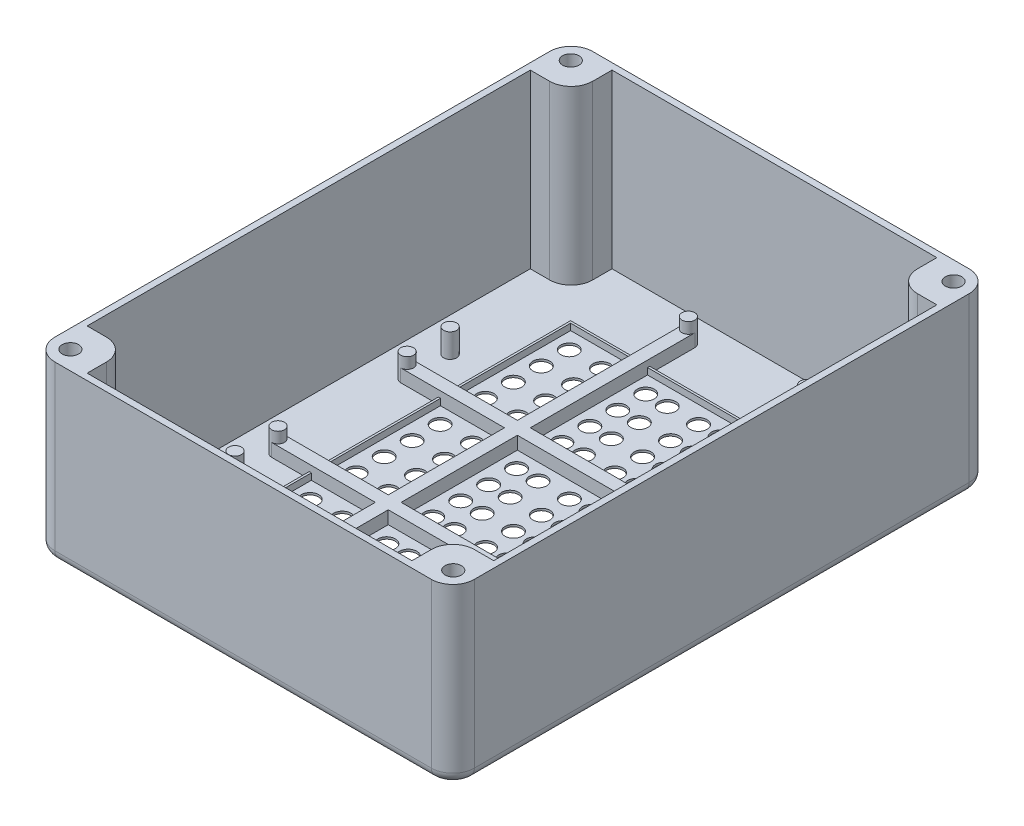
SolidWorks part; units mm, degrees
ref_plane "Front Plane" through (0, 0, 0) normal (0, 0, 1) x (1, 0, 0)
ref_plane "Top Plane" through (0, 0, 0) normal (0, 1, 0) x (1, 0, 0)
ref_plane "Right Plane" through (0, 0, 0) normal (1, 0, 0) x (0, 0, -1)
sketch "Sketch1" plane through (0, 0, 0) normal (0, 1, 0) x (1, 0, 0)
  line L1 (-97.5, 125) -> (97.5, 125)
  line L2 (-97.5, 125) -> (-97.5, -125)
  line L3 (-97.5, -125) -> (97.5, -125)
  line L4 (97.5, 125) -> (97.5, -125)
  line L5 (-97.5, 125) -> (97.5, -125) construction
  line L6 (-97.5, -125) -> (97.5, 125) construction
  line L7 (-94.5, -122) -> (94.5, -122)
  line L8 (-94.5, -122) -> (-94.5, 122)
  line L9 (-94.5, 122) -> (94.5, 122)
  line L10 (94.5, -122) -> (94.5, 122)
  line L11 (-94.5, -122) -> (94.5, 122) construction
  line L12 (-94.5, 122) -> (94.5, -122) construction
  point P0 (0, 0)
  point P6 (0, 0)
  dimension "D1" = 250
  dimension "D2" = 195
  dimension "D3" = 189
  dimension "D4" = 244
extrude "Boss-Extrude1" add sketch "Sketch1" along normal blind 80
sketch "Sketch2" plane through (0, 0, 0) normal (0, -1, 0) x (1, 0, 0)
  line L1 (-97.5, -125) -> (97.5, -125)
  line L2 (-97.5, -125) -> (-97.5, 125)
  line L3 (-97.5, 125) -> (97.5, 125)
  line L4 (97.5, -125) -> (97.5, 125)
  line L5 (-97.5, -125) -> (-97.5, 125) construction
  line L6 (97.5, 125) -> (75.5, 125)
  line L7 (97.5, 125) -> (97.5, 103)
  line L8 (97.5, 103) -> (75.5, 103)
  line L9 (75.5, 125) -> (75.5, 103)
  line L10 (97.5, -125) -> (75.5, -125)
  line L11 (97.5, -125) -> (97.5, -103)
  line L12 (97.5, -103) -> (75.5, -103)
  line L13 (75.5, -125) -> (75.5, -103)
  line L14 (-97.5, -125) -> (-75.5, -125)
  line L15 (-97.5, -125) -> (-97.5, -103)
  line L16 (-97.5, -103) -> (-75.5, -103)
  line L17 (-75.5, -125) -> (-75.5, -103)
  line L18 (-97.5, 125) -> (-75.5, 125)
  line L19 (-97.5, 125) -> (-97.5, 103)
  line L20 (-97.5, 103) -> (-75.5, 103)
  line L21 (-75.5, 125) -> (-75.5, 103)
  dimension "D1" = 22
  dimension "D2" = 22
  dimension "D3" = 22
  dimension "D4" = 22
  dimension "D5" = 22
  dimension "D6" = 22
  dimension "D7" = 22
  dimension "D8" = 22
extrude "Boss-Extrude2" add sketch "Sketch2" against normal blind 80 contours L13 L1 L4 L12 | L1 L17 L16 L2 | L21 L3 L2 L20 | L3 L9 L8 L4
sketch "Sketch4" plane through (0, 0, 0) normal (0, 1, 0) x (1, 0, 0)
  line L0 (-27.5, -109.5) -> (-60.5, -109.5)
  line L1 (-78.75, 30) -> (78.75, 30)
  line L2 (-78.75, 30) -> (-78.75, -30)
  line L3 (-78.75, -30) -> (78.75, -30)
  line L4 (78.75, 30) -> (78.75, -30)
  line L5 (-78.75, 30) -> (78.75, -30) construction
  line L6 (-78.75, -30) -> (78.75, 30) construction
  line L7 (-27.5, -109.5) -> (27.5, -109.5)
  line L8 (-27.5, -109.5) -> (-27.5, 109.5)
  line L9 (-27.5, 109.5) -> (27.5, 109.5)
  line L10 (27.5, -109.5) -> (27.5, 109.5)
  line L11 (-27.5, -109.5) -> (27.5, 109.5) construction
  line L12 (-27.5, 109.5) -> (27.5, -109.5) construction
  line L13 (-78.75, 50) -> (78.75, 50)
  line L14 (-78.75, 50) -> (-78.75, -47)
  line L15 (-75.75, -50) -> (78.75, -50)
  line L16 (78.75, 50) -> (78.75, -50)
  line L17 (-78.75, 50) -> (78.75, -50) construction
  line L18 (-76.2174, -48.392) -> (78.75, 50) construction
  circle A0 centre (-27.5, 109.5) radius 3
  circle A1 centre (27.5, 109.5) radius 3
  circle A2 centre (-27.5, -109.5) radius 3
  circle A3 centre (27.5, -109.5) radius 3
  circle A4 centre (-78.75, 30) radius 3
  circle A5 centre (-78.75, -30) radius 3
  circle A6 centre (78.75, 30) radius 3
  circle A7 centre (78.75, -30) radius 3
  circle A8 centre (-78.75, 50) radius 3
  circle A9 centre (-78.75, -50) radius 3
  circle A10 centre (78.75, 50) radius 3
  circle A11 centre (78.75, -50) radius 3
  circle A12 centre (-60.5, -109.5) radius 4
  point P0 (0, 0)
  point P6 (0, 0)
  point P19 (0, 0)
  dimension "D4" = 157.5
  dimension "D6" = 6
  dimension "D7" = 6
  dimension "D8" = 6
  dimension "D1" = 157.5
  dimension "D2" = 60
  dimension "D3" = 55
  dimension "D5" = 100
extrude "Boss-Extrude3" add sketch "Sketch4" along normal blind 11.1
sketch "Sketch5" plane through (0, 0, 0) normal (0, -1, 0) x (1, 0, 0)
  line L1 (-97.5, 125) -> (97.5, 125)
  line L2 (-97.5, 125) -> (-97.5, -125)
  line L3 (-97.5, -125) -> (97.5, -125)
  line L4 (97.5, 125) -> (97.5, -125)
extrude "Boss-Extrude4" add sketch "Sketch5" along normal blind 1
fillet "Fillet1" radius 10 4 edges at (-75.5, 40, -103) (-75.5, 40, 103) (75.5, 40, 103) (75.5, 40, -103)
fillet "Fillet2" radius 10 4 edges at (97.5, 39.5, -125) (-97.5, 39.5, -125) (-97.5, 39.5, 125) (97.5, 39.5, 125)
fillet "Fillet3" radius 5 8 edges at (-94.5711, -1, 122.0711) (0, -1, 125) (94.5711, -1, 122.0711) (97.5, -1, 0) (94.5711, -1, -122.0711) (0, -1, -125) (-94.5711, -1, -122.0711) (-97.5, -1, 0)
sketch "Sketch6" plane through (0, -1, 0) normal (0, -1, 0) x (1, 0, 0)
  line L1 (-60.25, 87.5) -> (60.25, 87.5)
  line L2 (-60.25, 87.5) -> (-60.25, -87.5)
  line L3 (-60.25, -87.5) -> (60.25, -87.5)
  line L4 (60.25, 87.5) -> (60.25, -87.5)
  line L5 (-60.25, 87.5) -> (60.25, -87.5) construction
  line L6 (-60.25, -87.5) -> (60.25, 87.5) construction
  line L7 (-61.25, -88.5) -> (61.25, -88.5)
  line L8 (61.25, 88.5) -> (61.25, -88.5)
  line L9 (-61.25, 88.5) -> (61.25, 88.5)
  line L10 (-61.25, 88.5) -> (-61.25, -88.5)
  point P0 (0, 0)
  dimension "D1" = 175
  dimension "D2" = 120.5
  dimension "D3" = 1
extrude "Boss-Extrude5" add sketch "Sketch6" along normal blind 3
sketch "Sketch7" plane through (0, 0, 0) normal (0, 1, 0) x (1, 0, 0)
  line L0 (-24.5, -109.5) -> (-30.5, -109.5)
  line L1 (30.5, -109.5) -> (24.5, -109.5)
  line L2 (30.5, -109.5) -> (30.5, 109.1556)
  line L3 (30.5, 109.1556) -> (24.5, 109.1556)
  line L4 (24.5, -109.5) -> (24.5, 109.1556)
  line L5 (-24.5, -109.5) -> (-24.5, 109.6171)
  line L6 (-24.5, 109.6171) -> (-30.5, 109.6171)
  line L7 (-30.5, -109.5) -> (-30.5, 109.6171)
  line L8 (78.6793, -27.0251) -> (-78.8207, -27.0251)
  line L9 (78.75, 33) -> (-78.75, 33)
  line L10 (78.75, 33) -> (78.75, 27)
  line L11 (78.75, 27) -> (-78.75, 27)
  line L12 (-78.75, 33) -> (-78.75, 27)
  line L13 (78.6793, -27.0251) -> (78.6793, -33.0251)
  line L14 (78.6793, -33.0251) -> (-78.8207, -33.0251)
  line L15 (-78.8207, -27.0251) -> (-78.8207, -33.0251)
  circle A0 centre (27.5, -109.5) radius 3 construction
  circle A1 centre (-27.5, -109.5) radius 3 construction
  circle A2 centre (78.75, 30) radius 3 construction
  circle A3 centre (-78.75, 30) radius 3 construction
extrude "Boss-Extrude6" add sketch "Sketch7" along normal blind 6 contours L11 L12 L9 L10 | L8 L15 L14 L13 | L2 L3 L4 L1 | L5 L6 L7 L0
sketch "Sketch8" plane through (0, 0, 0) normal (0, 1, 0) x (1, 0, 0)
  line L0 (-61.25, 88.5) -> (-61.25, -88.5)
  line L1 (-60.25, 87.5) -> (60.25, 87.5)
  line L2 (-60.25, 87.5) -> (-60.25, -87.5)
  line L3 (-60.25, -87.5) -> (60.25, -87.5)
  line L4 (60.25, 87.5) -> (60.25, -87.5)
  line L5 (-60.25, 87.5) -> (60.25, -87.5) construction
  line L6 (-60.25, -87.5) -> (60.25, 87.5) construction
  line L7 (-61.25, -88.5) -> (61.25, -88.5)
  line L8 (61.25, 88.5) -> (61.25, -88.5)
  line L9 (-61.25, 88.5) -> (61.25, 88.5)
  point P0 (0, 0)
  dimension "D1" = 120.5
  dimension "D2" = 175
  dimension "D3" = 1
extrude "Boss-Extrude7" add sketch "Sketch8" along normal blind 3
sketch "Sketch9" plane through (0, 0, 0) normal (0, 1, 0) x (1, 0, 0)
  line L1 (88.9739, 116.2905) -> (-88.9739, 116.2905)
  line L2 (88.9739, 116.2905) -> (88.9739, -116.2905)
  line L3 (88.9739, -116.2905) -> (-88.9739, -116.2905)
  line L4 (-88.9739, 116.2905) -> (-88.9739, -116.2905)
  line L5 (88.9739, 116.2905) -> (-88.9739, -116.2905) construction
  line L6 (88.9739, -116.2905) -> (-88.9739, 116.2905) construction
  circle A0 centre (-88.9739, -116.2905) radius 3.8081
  circle A1 centre (-88.9739, 116.2905) radius 3.8081
  circle A2 centre (88.9739, -116.2905) radius 3.8081
  circle A3 centre (88.9739, 116.2905) radius 3.8081
  point P0 (0, 0)
extrude "Cut-Extrude1" cut sketch "Sketch9" against normal blind 50 from surface at 80 contours L2 A3 L1 | L1 A3 L2 | L1 A1 L4 | L4 A1 L1 | L4 A0 L3 | L3 A0 L4 | L3 A2 L2 | L2 A2 L3 starting at face at (0, 80, 0)
sketch "Sketch10" plane through (0, 11.1, 0) normal (0, 1, 0) x (1, 0, 0)
  circle A0 centre (-60.5, -109.5) radius 4
extrude "Cut-Extrude2" cut sketch "Sketch10" against normal through all contours A0
sketch "Sketch11" plane through (0, 0, 0) normal (0, 1, 0) x (1, 0, 0)
  circle A0 centre (52.8125, -80.0625) radius 4
  circle A1 centre (37.8125, -80.0625) radius 4
  circle A2 centre (37.8125, -67.0625) radius 4
  circle A3 centre (37.8125, -54.0625) radius 4
  circle A4 centre (37.8125, -41.0625) radius 4
  circle A5 centre (52.8125, -67.0625) radius 4
  circle A6 centre (52.8125, -54.0625) radius 4
  circle A7 centre (52.8125, -41.0625) radius 4
  circle A8 centre (37.8125, -19.5876) radius 3.9375
  circle A9 centre (52.8125, -19.5876) radius 3.9375
  circle A10 centre (37.8125, -6.5876) radius 3.9375
  circle A11 centre (37.8125, 6.4124) radius 3.9375
  circle A12 centre (37.8125, 19.4124) radius 3.9375
  circle A13 centre (52.8125, -6.5876) radius 3.9375
  circle A14 centre (52.8125, 6.4124) radius 3.9375
  circle A15 centre (52.8125, 19.4124) radius 3.9375
  circle A16 centre (37.8125, 40.4375) radius 3.9375
  circle A17 centre (52.8125, 40.4375) radius 3.9375
  circle A18 centre (37.8125, 53.4375) radius 3.9375
  circle A19 centre (37.8125, 66.4375) radius 3.9375
  circle A20 centre (37.8125, 79.4375) radius 3.9375
  circle A21 centre (52.8125, 53.4375) radius 3.9375
  circle A22 centre (52.8125, 66.4375) radius 3.9375
  circle A23 centre (52.8125, 79.4375) radius 3.9375
  circle A24 centre (17.2, -80.0625) radius 4
  circle A25 centre (7.2, -80.0625) radius 4
  circle A26 centre (7.2, -67.0625) radius 4
  circle A27 centre (7.2, -54.0625) radius 4
  circle A28 centre (7.2, -41.0625) radius 4
  circle A29 centre (17.2, -67.0625) radius 4
  circle A30 centre (17.2, -54.0625) radius 4
  circle A31 centre (17.2, -41.0625) radius 4
  circle A32 centre (17.2625, -19.5876) radius 3.9375
  circle A33 centre (7.2625, -19.5876) radius 3.9375
  circle A34 centre (7.2625, -6.5876) radius 3.9375
  circle A35 centre (7.2625, 6.4124) radius 3.9375
  circle A36 centre (7.2625, 19.4124) radius 3.9375
  circle A37 centre (17.2625, -6.5876) radius 3.9375
  circle A38 centre (17.2625, 6.4124) radius 3.9375
  circle A39 centre (17.2625, 19.4124) radius 3.9375
  circle A40 centre (17.2625, 40.4375) radius 3.9375
  circle A41 centre (7.2625, 40.4375) radius 3.9375
  circle A42 centre (7.2625, 53.4375) radius 3.9375
  circle A43 centre (7.2625, 66.4375) radius 3.9375
  circle A44 centre (7.2625, 79.4375) radius 3.9375
  circle A45 centre (17.2625, 53.4375) radius 3.9375
  circle A46 centre (17.2625, 66.4375) radius 3.9375
  circle A47 centre (17.2625, 79.4375) radius 3.9375
  circle A48 centre (-17.2625, 79.4375) radius 3.9375
  circle A49 centre (-17.2625, 66.4375) radius 3.9375
  circle A50 centre (-17.2625, 53.4375) radius 3.9375
  circle A51 centre (-7.2625, 79.4375) radius 3.9375
  circle A52 centre (-7.2625, 66.4375) radius 3.9375
  circle A53 centre (-7.2625, 53.4375) radius 3.9375
  circle A54 centre (-7.2625, 40.4375) radius 3.9375
  circle A55 centre (-17.2625, 40.4375) radius 3.9375
  circle A56 centre (-17.2625, 19.4124) radius 3.9375
  circle A57 centre (-17.2625, 6.4124) radius 3.9375
  circle A58 centre (-17.2625, -6.5876) radius 3.9375
  circle A59 centre (-7.2625, 19.4124) radius 3.9375
  circle A60 centre (-7.2625, 6.4124) radius 3.9375
  circle A61 centre (-7.2625, -6.5876) radius 3.9375
  circle A62 centre (-7.2625, -19.5876) radius 3.9375
  circle A63 centre (-17.2625, -19.5876) radius 3.9375
  circle A64 centre (-17.2, -41.0625) radius 4
  circle A65 centre (-17.2, -54.0625) radius 4
  circle A66 centre (-17.2, -67.0625) radius 4
  circle A67 centre (-7.2, -41.0625) radius 4
  circle A68 centre (-7.2, -54.0625) radius 4
  circle A69 centre (-7.2, -67.0625) radius 4
  circle A70 centre (-7.2, -80.0625) radius 4
  circle A71 centre (-17.2, -80.0625) radius 4
  circle A72 centre (-52.8125, 79.4375) radius 3.9375
  circle A73 centre (-52.8125, 66.4375) radius 3.9375
  circle A74 centre (-52.8125, 53.4375) radius 3.9375
  circle A75 centre (-37.8125, 79.4375) radius 3.9375
  circle A76 centre (-37.8125, 66.4375) radius 3.9375
  circle A77 centre (-37.8125, 53.4375) radius 3.9375
  circle A78 centre (-52.8125, 40.4375) radius 3.9375
  circle A79 centre (-37.8125, 40.4375) radius 3.9375
  circle A80 centre (-52.8125, 19.4124) radius 3.9375
  circle A81 centre (-52.8125, 6.4124) radius 3.9375
  circle A82 centre (-52.8125, -6.5876) radius 3.9375
  circle A83 centre (-37.8125, 19.4124) radius 3.9375
  circle A84 centre (-37.8125, 6.4124) radius 3.9375
  circle A85 centre (-37.8125, -6.5876) radius 3.9375
  circle A86 centre (-52.8125, -19.5876) radius 3.9375
  circle A87 centre (-37.8125, -19.5876) radius 3.9375
  circle A88 centre (-52.8125, -41.0625) radius 4
  circle A89 centre (-52.8125, -54.0625) radius 4
  circle A90 centre (-52.8125, -67.0625) radius 4
  circle A91 centre (-37.8125, -41.0625) radius 4
  circle A92 centre (-37.8125, -54.0625) radius 4
  circle A93 centre (-37.8125, -67.0625) radius 4
  circle A94 centre (-37.8125, -80.0625) radius 4
  circle A95 centre (-52.8125, -80.0625) radius 4
  dimension "D1" = 2
  dimension "D5" = 2
  dimension "D7" = 2
  dimension "D2" = 4
  dimension "D3" = 2
  dimension "D4" = 2
  dimension "D6" = 4
  dimension "D9" = 4
  dimension "D11" = 4
  dimension "D12" = 4
  dimension "D10" = 2
  dimension "D13" = 4
extrude "Cut-Extrude3" cut sketch "Sketch11" against normal through all
